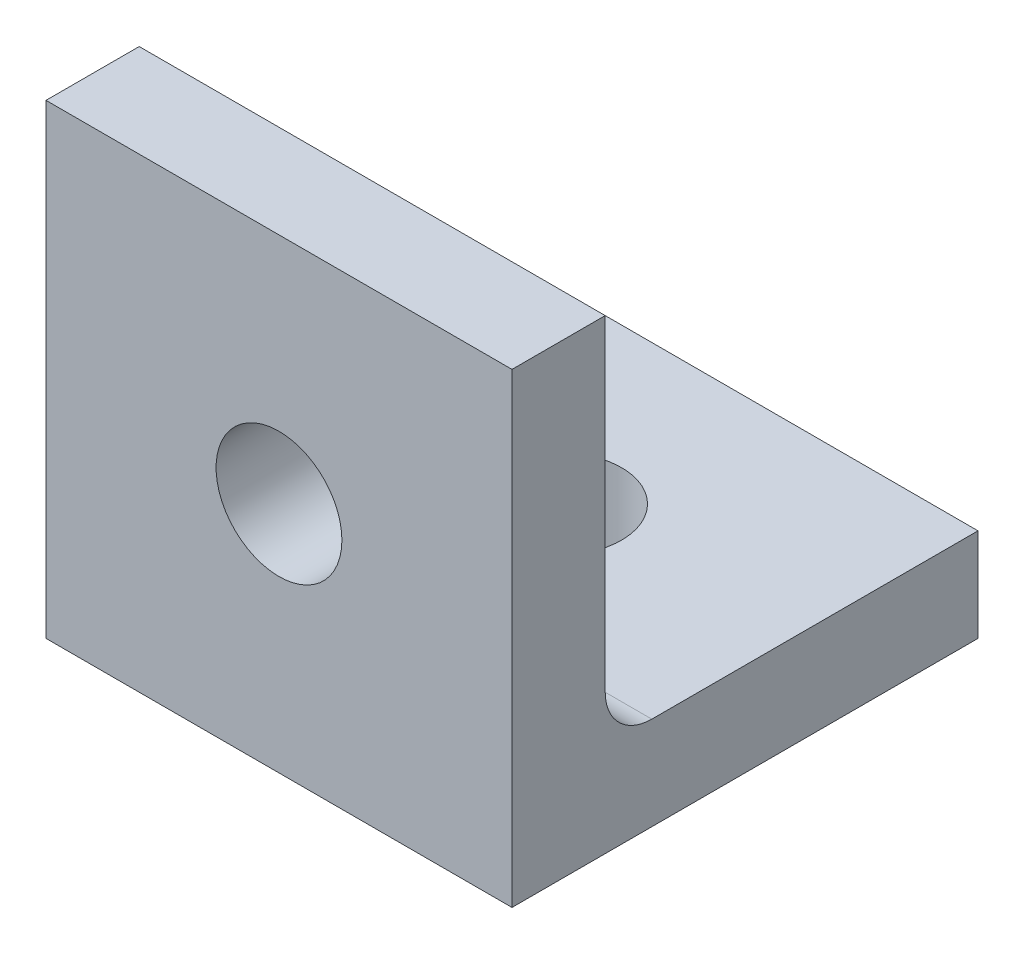
SolidWorks part; units mm, degrees
ref_plane "Front Plane" through (0, 0, 0) normal (0, 0, 1) x (1, 0, 0)
ref_plane "Top Plane" through (0, 0, 0) normal (0, 1, 0) x (1, 0, 0)
ref_plane "Right Plane" through (0, 0, 0) normal (1, 0, 0) x (0, 0, -1)
sketch "Sketch1" plane through (0, 0, 0) normal (0, 0, 1) x (1, 0, 0)
  line L0 (0, 0) -> (25.4, -25.4) construction
  line L1 (0, 0) -> (25.4, 0)
  line L2 (0, 0) -> (0, -25.4)
  line L3 (0, -25.4) -> (25.4, -25.4)
  line L4 (25.4, 0) -> (25.4, -25.4)
  circle A0 centre (12.7, -12.7) radius 3.429
  dimension "D3" = 6.858
  dimension "D1" = 25.4
  dimension "D2" = 25.4
extrude "Boss-Extrude1" add sketch "Sketch1" along normal mid plane 5.08
sketch "Sketch3" plane through (0, 0, 2.54) normal (0, 0, 1) x (1, 0, 0)
  line L5 (25.4, -25.4) -> (25.4, 0) construction
  line L6 (0, -25.4) -> (25.4, -25.4)
  line L7 (0, -25.4) -> (0, -20.32)
  line L8 (0, -20.32) -> (25.4, -20.32)
  line L9 (25.4, -25.4) -> (25.4, -20.32)
  dimension "D1" = 5.08
extrude "Boss-Extrude2" add sketch "Sketch3" against normal blind 25.4
sketch "Sketch4" plane through (0, -20.32, 0) normal (0, 1, 0) x (1, 0, 0)
  line L0 (25.4, 2.54) -> (0, 22.86) construction
  circle A1 centre (12.7, 12.7) radius 3.429
  dimension "D1" = 6.858
extrude "Cut-Extrude1" cut sketch "Sketch4" against normal up to surface (5.08 mm away) up to face at (12.7, -25.4, -10.16)
fillet "Fillet1" radius 2.54 1 edges at (12.7, -20.32, -2.54)
